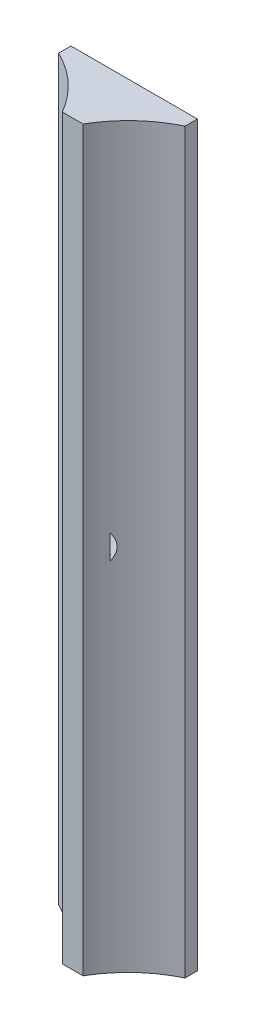
SolidWorks part; units mm, degrees
ref_plane "Front" through (0, 0, 0) normal (0, 0, 1) x (1, 0, 0)
ref_plane "Top" through (0, 0, 0) normal (0, 1, 0) x (1, 0, 0)
ref_plane "Right" through (0, 0, 0) normal (1, 0, 0) x (0, 0, -1)
sketch "Sketch1" plane through (0, 0, 0) normal (0, 1, 0) x (1, 0, 0)
  line L0 (-0.8397, 0) -> (0.8397, 0)
  line L1 (5.1411, 4) -> (5.1411, 5)
  line L2 (5.1411, 5) -> (-5.1411, 5)
  line L3 (-5.1411, 5) -> (-5.1411, 4)
  arc A0 (0.8397, 0) -> (5.1411, 4) centre (9.5, -5) cw
  arc A1 (-5.1411, 4) -> (-0.8397, 0) centre (-9.5, -5) cw
  point P9 (0, 5)
  point P10 (0, 0)
  dimension "D1" = 10
  dimension "D6" = 5
  dimension "D2" = 19
  dimension "D3" = 10
  dimension "D4" = 1
extrude "Boss-Extrude1" add sketch "Sketch1" along normal mid plane 60
sketch "Sketch3" plane through (0, 0, -5) normal (0, 0, -1) x (-1, 0, 0)
  line L0 (0, -30) -> (0, 30) construction
  line L1 (-5.1411, -30) -> (5.1411, -30) construction
  line L2 (-5.1411, 30) -> (5.1411, 30) construction
  point P6 (0, 0)
  dimension "D2" = 30
sketch "Sketch6" plane through (0, 0, -5) normal (0, 0, -1) x (-1, 0, 0)
  point P0 (0, 0)
hole_wizard "#24 (0.152) Diameter Hole1" positions "Sketch7" profile "Sketch8" hole size "#24" standard "ANSI Inch"
sketch "Sketch7" plane through (0, 0, -5) normal (0, 0, -1) x (-1, 0, 0)
  point P0 (0, 0)
sketch "Sketch8" plane through (0, 0, -5) normal (1, 0, 0) x (0, 1, 0)
  line L0 (0, 0) -> (0, 3.7)
  line L1 (0, 3.7) -> (2, 3.7)
  line L2 (2, 3.7) -> (2, 2.8601)
  line L3 (2, 2.8601) -> (2.2, 0)
  line L5 (2.2, 0) -> (0, 0)
  line L6 (-2, 2.8601) -> (-2.2, 0) construction
  line L10 (0, 3.7) -> (-2, 3.7) construction
  line L11 (0, -6.35) -> (0, 107.95) construction
  dimension "Hole Dia." = 4
  dimension "Hole Depth" = 3.7
  dimension "Near C'Sink Dia." = 4.4
  dimension "Near C'Sink Angle" = 8
  dimension "Drill Angle" = 180
